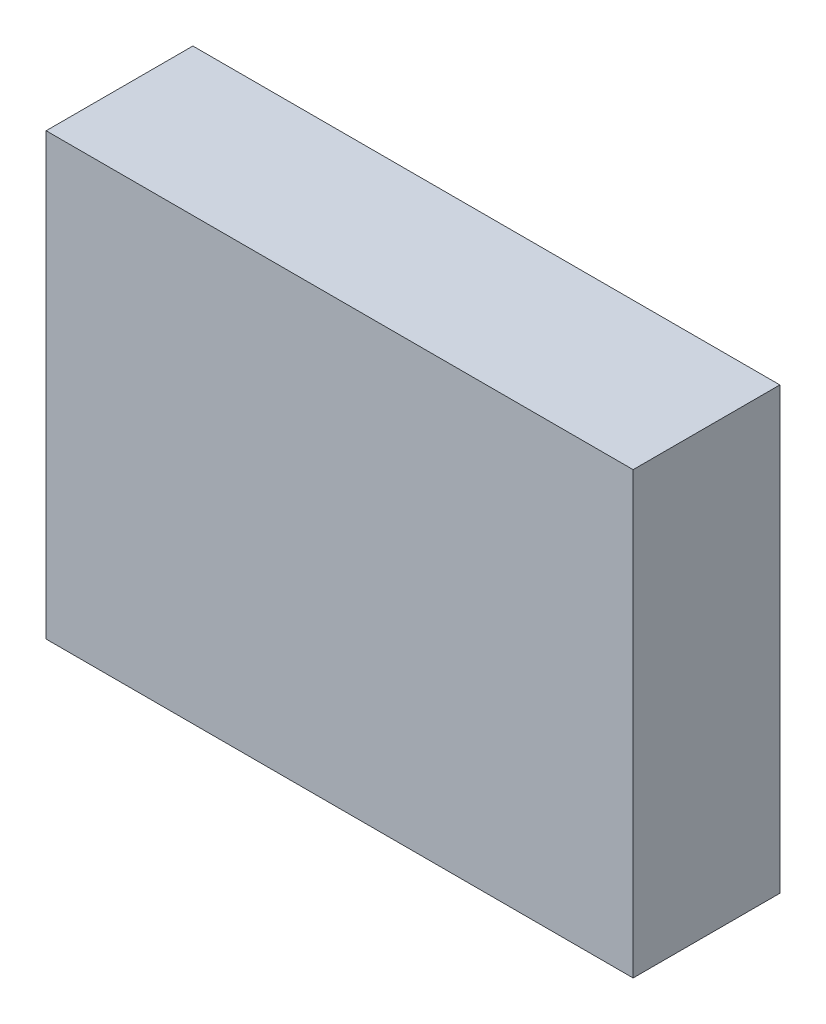
SolidWorks part; units mm, degrees
ref_plane "前视基准面" through (0, 0, 0) normal (0, 0, 1) x (1, 0, 0)
ref_plane "上视基准面" through (0, 0, 0) normal (0, 1, 0) x (1, 0, 0)
ref_plane "右视基准面" through (0, 0, 0) normal (1, 0, 0) x (0, 0, -1)
other "Configuration Table"
sketch "草图1" plane through (0, 0, 0) normal (0, 0, 1) x (1, 0, 0)
  circle A0 centre (0, 0) radius 37.5
  dimension "D1" = 75
extrude "凸台-拉伸1" add sketch "草图1" along normal blind 3
sketch "草图2" plane through (0, 0, 0) normal (0, 0, -1) x (-1, 0, 0)
  circle A0 centre (0, 0) radius 25 construction
  circle A1 centre (0, 0) radius 25
extrude "切除-拉伸1" cut sketch "草图2" against normal blind 3
sketch "草图3" plane through (0, 0, 3) normal (0, 0, 1) x (1, 0, 0)
  line L0 (0, -30) -> (0, 0) construction
  circle A0 centre (0, -30) radius 1.5
  dimension "D1" = 3
  dimension "D2" = 30
extrude "切除-拉伸2" cut sketch "草图3" against normal blind 13
pattern_circular "阵列(圆周)1" count 8 over 360 about axis through (0, 0, 0) along (0, 0, 1) of "切除-拉伸2"
sketch "草图4" plane through (0, 0, 3) normal (0, 0, 1) x (1, 0, 0)
  circle A0 centre (0, 0) radius 20
  circle A1 centre (0, 0) radius 25 construction
  circle A2 centre (0, 0) radius 25
extrude "凸台-拉伸2" add sketch "草图4" against normal blind 10 and the other way blind 5
sketch "草图6" plane through (0, 0, 3) normal (0, 0, 1) x (1, 0, 0)
  line L1 (100, 75) -> (-100, 75)
  line L2 (100, 75) -> (100, -75)
  line L3 (100, -75) -> (-100, -75)
  line L4 (-100, 75) -> (-100, -75)
  line L5 (100, 75) -> (-100, -75) construction
  line L6 (100, -75) -> (-100, 75) construction
  point P0 (0, 0)
  dimension "D1" = 150
  dimension "D2" = 200
extrude "凸台-拉伸3" add sketch "草图6" along normal blind 50
